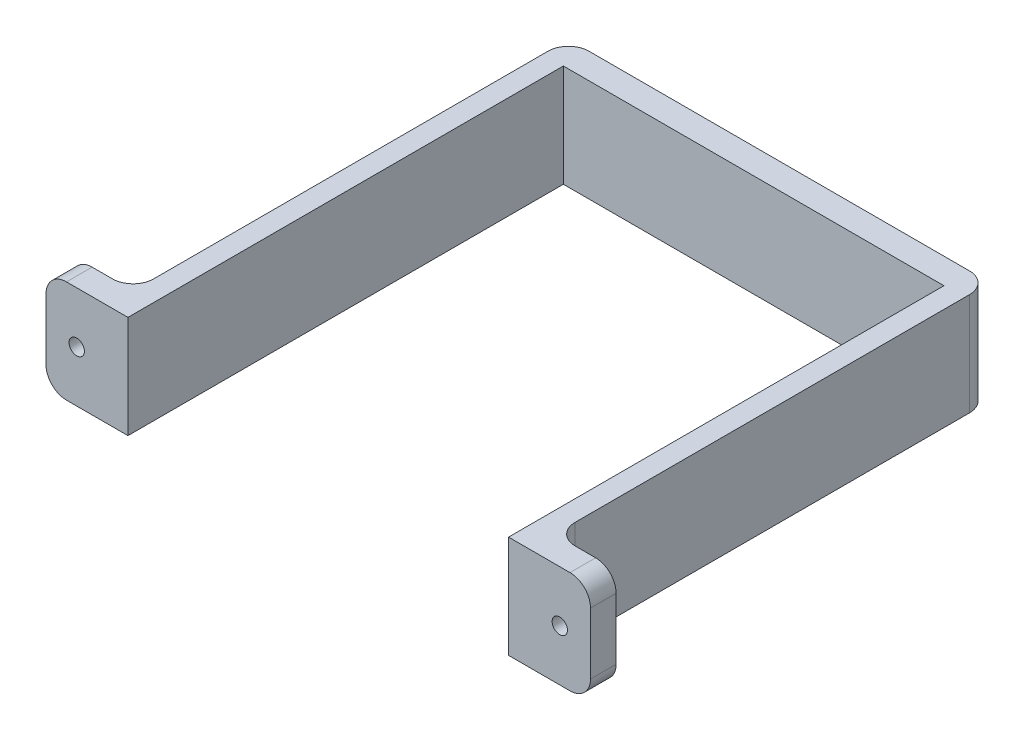
SolidWorks part; units mm, degrees
ref_plane "Piano frontale" through (0, 0, 0) normal (0, 0, 1) x (1, 0, 0)
ref_plane "Piano superiore" through (0, 0, 0) normal (0, 1, 0) x (1, 0, 0)
ref_plane "Piano destro" through (0, 0, 0) normal (1, 0, 0) x (0, 0, -1)
sketch "Schizzo1" plane through (0, 0, 0) normal (0, 0, 1) x (1, 0, 0)
  line L1 (-37.15, 10) -> (37.15, 10)
  line L2 (-37.15, 10) -> (-37.15, -10)
  line L3 (-37.15, -10) -> (37.15, -10)
  line L4 (37.15, 10) -> (37.15, -10)
  line L5 (-37.15, 10) -> (37.15, -10) construction
  line L6 (-37.15, -10) -> (37.15, 10) construction
  point P0 (0, 0)
  dimension "D1" = 20
  dimension "D2" = 74.3
extrude "Estrusione-Estrusione1" add sketch "Schizzo1" along normal blind 5
sketch "Schizzo2" plane through (0, 0, 5) normal (0, 0, 1) x (1, 0, 0)
  line L1 (-37.15, -10) -> (-41.15, -10)
  line L2 (-37.15, -10) -> (-37.15, 10)
  line L3 (-37.15, 10) -> (-41.15, 10)
  line L4 (-41.15, -10) -> (-41.15, 10)
  line L5 (37.15, 10) -> (41.15, 10)
  line L6 (37.15, 10) -> (37.15, -10)
  line L7 (37.15, -10) -> (41.15, -10)
  line L8 (41.15, 10) -> (41.15, -10)
  dimension "D1" = 4
  dimension "D2" = 4
extrude "Estrusione-Estrusione2" add sketch "Schizzo2" along normal blind 85 separate body
sketch "Schizzo3" plane through (0, 0, 5) normal (0, 0, -1) x (-1, 0, 0)
  line L1 (-41.15, 10) -> (-37.15, 10)
  line L2 (-41.15, 10) -> (-41.15, -10)
  line L3 (-41.15, -10) -> (-37.15, -10)
  line L4 (-37.15, 10) -> (-37.15, -10)
  line L5 (37.15, 10) -> (41.15, 10)
  line L6 (37.15, 10) -> (37.15, -10)
  line L7 (37.15, -10) -> (41.15, -10)
  line L8 (41.15, 10) -> (41.15, -10)
extrude "Estrusione-Estrusione3" add sketch "Schizzo3" along normal blind 5
sketch "Schizzo4" plane through (41.15, 0, 0) normal (1, 0, 0) x (0, 0, -1)
  line L0 (0, -10) -> (-90, -10) construction
  line L1 (-90, 10) -> (-85, 10)
  line L2 (-90, 10) -> (-90, -10)
  line L3 (-90, -10) -> (-85, -10)
  line L4 (-85, 10) -> (-85, -10)
  dimension "D1" = 5
extrude "Estrusione-Estrusione4" add sketch "Schizzo4" along normal blind 12
sketch "Schizzo5" plane through (0, 0, 85) normal (0, 0, -1) x (-1, 0, 0)
  line L0 (-53.15, 10) -> (-41.15, -10) construction
  line L1 (-41.15, -10) -> (-41.15, 10) construction
  line L2 (-41.15, 10) -> (-53.15, -10) construction
  circle A0 centre (-47.15, 0) radius 1.5
  dimension "D1" = 3
extrude "Taglio-Estrusione1" cut sketch "Schizzo5" against normal through all
sketch "Schizzo6" plane through (-41.15, 0, 0) normal (-1, 0, 0) x (0, 0, 1)
  line L0 (0, -10) -> (90, -10) construction
  line L1 (90, 10) -> (85, 10)
  line L2 (90, 10) -> (90, -10)
  line L3 (90, -10) -> (85, -10)
  line L4 (85, 10) -> (85, -10)
  dimension "D1" = 5
extrude "Estrusione-Estrusione5" add sketch "Schizzo6" along normal blind 12
mirror "Specchia13" about plane through (0, 0, 0) normal (1, 0, 0) of "Taglio-Estrusione1"
fillet "Raccordo1" radius 4 8 edges at (41.15, 0, 0) (53.15, 10, 87.5) (53.15, -10, 87.5) (41.15, 0, 85) (-41.15, 0, 0) (-53.15, 10, 87.5) (-53.15, -10, 87.5) (-41.15, 0, 85)
